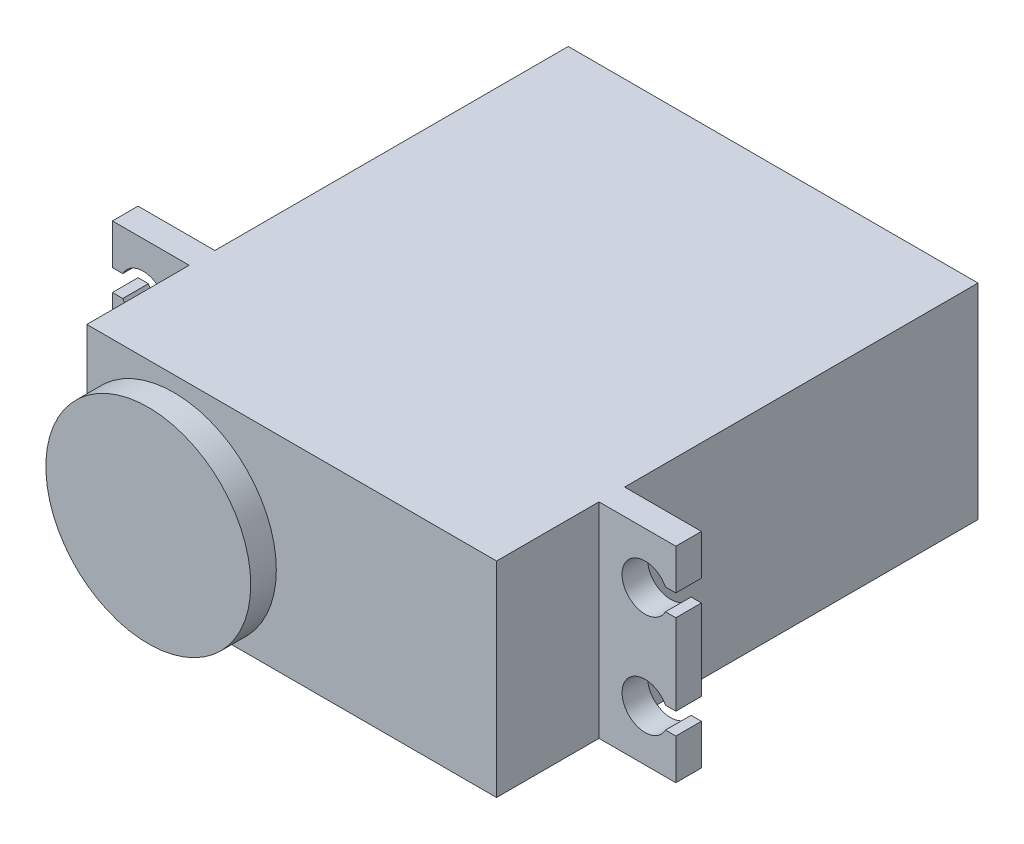
SolidWorks part; units mm, degrees
ref_plane "Ground" through (0, 0, 0) normal (0, 0, 1) x (1, 0, 0)
ref_plane "Right" through (0, 0, 0) normal (0, 1, 0) x (1, 0, 0)
ref_plane "Front" through (0, 0, 0) normal (1, 0, 0) x (0, 0, -1)
sketch "Sketch1" plane through (0, 0, 0) normal (1, 0, 0) x (0, 0, -1)
  line L1 (0, 0) -> (47, 0)
  line L2 (0, 0) -> (0, 20)
  line L3 (0, 20) -> (47, 20)
  line L4 (47, 0) -> (47, 20)
  dimension "D1" = 47
  dimension "D2" = 20
extrude "Boss-Extrude1" add sketch "Sketch1" along normal blind 40
sketch "Sketch2" plane through (0, 0, 0) normal (0, 0, 1) x (1, 0, 0)
  line L0 (0, 10) -> (10, 10) construction
  line L1 (0, 20) -> (0, 0) construction
  line L2 (40, 20) -> (40, 0) construction
  line L6 (40, 0) -> (0, 0) construction
  circle A1 centre (10, 10) radius 2.95
  point P9 (34, 10)
  point P10 (40, 10)
  dimension "D3" = 5.9
  dimension "D1" = 10
  dimension "D2" = 10
extrude "Boss-Extrude5" add sketch "Sketch2" along normal blind 4
sketch "Sketch5" plane through (0, 0, 4) normal (0, 0, 1) x (1, 0, 0)
  circle A0 centre (10, 10) radius 10
  circle A1 centre (10, 10) radius 2.95
  circle A2 centre (10, 10) radius 2.95 construction
  dimension "D2" = 20
  dimension "D1" = 0
extrude "Boss-Extrude6" add sketch "Sketch5" against normal blind 2.5
sketch "Sketch6" plane through (0, 0, 0) normal (-1, 0, 0) x (0, 0, 1)
  line L2 (-12.5, 0) -> (-10, 0)
  line L3 (-12.5, 0) -> (-12.5, 20)
  line L4 (0, 0) -> (0, 20)
  line L5 (0, 20) -> (-47, 20)
  line L6 (-47, 20) -> (-47, 0)
  line L7 (-47, 0) -> (0, 0)
  line L8 (0, 0) -> (0, 20)
  line L9 (0, 20) -> (-47, 20)
  line L10 (-47, 20) -> (-47, 0)
  line L11 (-47, 0) -> (0, 0)
  line L12 (-12.5, 20) -> (-10, 20)
  line L13 (-10, 0) -> (-10, 20)
  line L14 (-12.5, 0) -> (-10, 20) construction
  line L15 (-12.5, 20) -> (-10, 0) construction
  point P6 (-11.25, 10)
  line M10 (-47, 0) -> (0, 0)
  dimension "D2" = 2.5
  dimension "D3" = 10
  dimension "D1" = 0
extrude "Boss-Extrude7" add sketch "Sketch6" along normal blind 7.5 contours L13 L9 L3 M10
ref_plane "Plane1" through (20, 0, 0) normal (1, 0, 0) x (0, 0, -1)
sketch "Sketch7" plane through (0, 0, -10) normal (0, 0, 1) x (1, 0, 0)
  line L0 (-7.5, 0) -> (-7.5, 20) construction
  line L1 (-4.5, 15) -> (-4.5, 5) construction
  line L2 (-7.5, 0) -> (-7.5, 20) construction
  line L3 (-6.49, 16.05) -> (-7.5, 16.05)
  line L4 (-7.5, 16.05) -> (-7.5, 13.95)
  line L5 (-7.5, 13.95) -> (-6.49, 13.95)
  line L6 (-7.5, 6.05) -> (-7.5, 3.95)
  line L7 (-7.5, 6.05) -> (-6.49, 6.05)
  line L8 (-7.5, 3.95) -> (-6.49, 3.95)
  circle A0 centre (-4.5, 15) radius 2.25
  circle A1 centre (-4.5, 5) radius 2.25
  point P6 (-7.5, 10)
  point P7 (-4.5, 10)
  point P11 (-7.5, 15)
  point P15 (-7.5, 5)
  line M8 (-7.5, 20) -> (-7.5, 0)
  dimension "D1" = 4.5
  dimension "D2" = 3
  dimension "D3" = 10
  dimension "D4" = 2.1
extrude "Cut-Extrude1" cut sketch "Sketch7" against normal up to next contours A0 | A0 L3 L5 M8 | A1 | A1 L7 L8 M8
mirror "Mirror1" about plane through (20, 0, 0) normal (1, 0, 0) of "Boss-Extrude7", "Cut-Extrude1"
